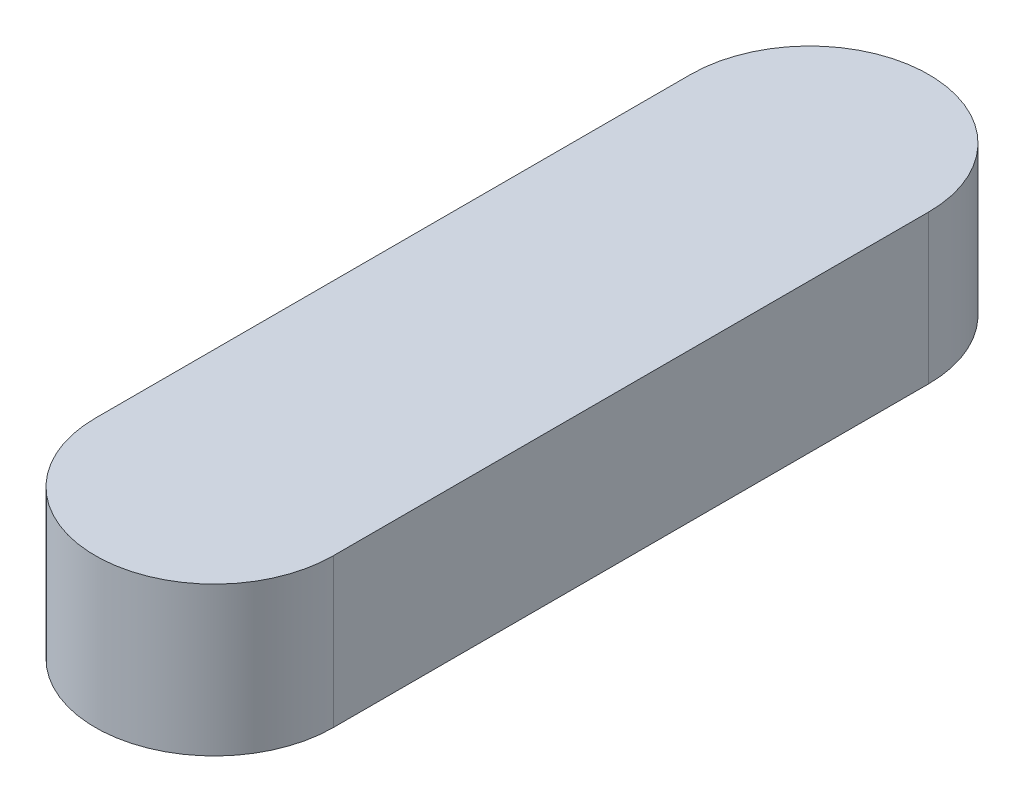
SolidWorks part; units mm, degrees
ref_plane "Front Plane" through (0, 0, 0) normal (0, 0, 1) x (1, 0, 0)
ref_plane "Top Plane" through (0, 0, 0) normal (0, 1, 0) x (1, 0, 0)
ref_plane "Right Plane" through (0, 0, 0) normal (1, 0, 0) x (0, 0, -1)
sketch "Sketch1" plane through (0, 0, 0) normal (1, 0, 0) x (0, 0, -1)
  line L0 (-28, 5) -> (-28, -5) construction
  line L1 (-28, 5) -> (28, 5) construction
  line L3 (0, 1.65) -> (0, -1.65) construction
  line L4 (1.65, 0) -> (-1.65, 0) construction
  point P0 (-28, 0)
  point P4 (0, 5)
  dimension "Height" = 10
  dimension "Length" = 56
sketch "Sketch3" plane through (0, 0, 0) normal (0, 1, 0) x (1, 0, 0)
  line L0 (0, -20) -> (0, 20) construction
  line L1 (-8, -20) -> (-8, 20)
  line L2 (8, -20) -> (8, 20)
  line L3 (-1.65, 0) -> (1.65, 0) construction
  arc A0 (-8, -20) -> (8, -20) centre (0, -20) ccw
  arc A1 (8, 20) -> (-8, 20) centre (0, 20) ccw
  point P3 (0, 0)
  point P8 (-8, 12)
  point P12 (8, -12)
  dimension "Width" = 16
  dimension "D1" = 16
  dimension "D2" = 16
sketch "Sketch4" plane through (0, 0, 0) normal (0, 1, 0) x (1, 0, 0)
  line L0 (-8, -20) -> (-8, 20) construction
  line L1 (8, -20) -> (8, 20) construction
  line L2 (-8, -20) -> (-8, 20)
  line L3 (8, -20) -> (8, 20)
  arc A0 (8, 20) -> (-8, 20) centre (0, 20) ccw construction
  arc A1 (-8, -20) -> (8, -20) centre (0, -20) ccw construction
  arc A2 (8, 20) -> (-8, 20) centre (0, 20) ccw
  arc A3 (-8, -20) -> (8, -20) centre (0, -20) ccw
extrude "Boss-Extrude1" add sketch "Sketch4" against normal up to vertex (5 mm away) from vertex at 5 starting at point (0, 5, 28)
equation "\"D1@Sketch3\"=\"Width@Sketch3\""
equation "\"D2@Sketch3\"=\"D1@Sketch3\""
